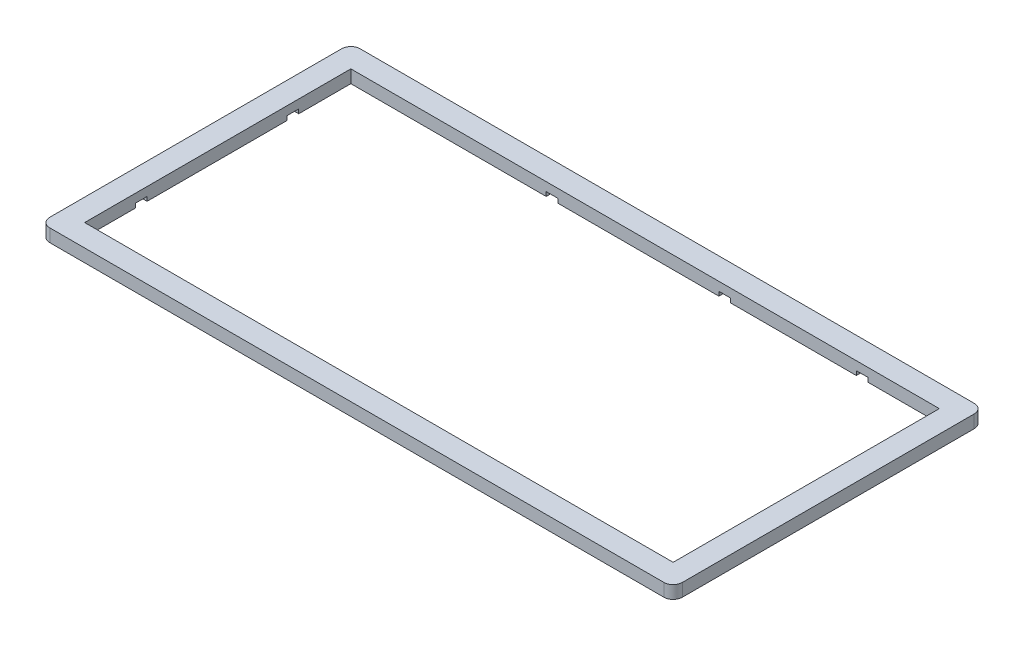
SolidWorks part; units mm, degrees
ref_plane "Front Plane" through (0, 0, 0) normal (0, 0, 1) x (1, 0, 0)
ref_plane "Top Plane" through (0, 0, 0) normal (0, 1, 0) x (1, 0, 0)
ref_plane "Right Plane" through (0, 0, 0) normal (1, 0, 0) x (0, 0, -1)
sketch "Sketch1" plane through (0, 0, 0) normal (0, 1, 0) x (1, 0, 0)
  line L0 (-142.8618, 0) -> (191.3602, 0) construction
  line L1 (0, 90.7825) -> (0, -132.7671) construction
  line L2 (-160.275, 78.7825) -> (160.275, 78.7825)
  line L3 (160.275, 78.7825) -> (160.275, -66.2175)
  line L4 (160.275, -66.2175) -> (-160.275, -66.2175)
  line L5 (-160.275, -66.2175) -> (-160.275, 78.7825)
  line L6 (-172.275, 90.7825) -> (172.275, 90.7825)
  line L7 (172.275, 90.7825) -> (172.275, -78.2175)
  line L8 (172.275, -78.2175) -> (-172.275, -78.2175)
  line L9 (-172.275, -78.2175) -> (-172.275, 90.7825)
  dimension "D1" = 320.55
  dimension "D2" = 145
  dimension "D3" = 12
  dimension "D4" = 12
  dimension "D5" = 12
  dimension "D6" = 12
extrude "Boss-Extrude1" add sketch "Sketch1" along normal blind 7
sketch "Sketch3" plane through (0, 0, 0) normal (0, -1, 0) x (1, 0, 0)
  line L0 (-22.72, -82.0825) -> (-47.57, -82.0825)
  line L1 (-22.72, -86.5825) -> (-22.72, -82.0825)
  line L2 (-78.72, -86.5825) -> (-22.72, -86.5825)
  line L3 (-78.72, -82.0825) -> (-78.72, -86.5825)
  line L4 (-53.87, -82.0825) -> (-78.72, -82.0825)
  line L5 (-53.87, -78.7825) -> (-53.87, -82.0825)
  line L6 (-47.57, -78.7825) -> (-53.87, -78.7825)
  line L7 (-47.57, -82.0825) -> (-47.57, -78.7825)
  line L16 (160.275, -78.7825) -> (-160.275, -78.7825) construction
  line L17 (-130.175, 66.2175) -> (-123.875, 66.2175)
  line L18 (146.225, -82.0825) -> (121.375, -82.0825)
  line L19 (146.225, -86.5825) -> (146.225, -82.0825)
  line L20 (90.225, -86.5825) -> (146.225, -86.5825)
  line L21 (90.225, -82.0825) -> (90.225, -86.5825)
  line L22 (115.075, -82.0825) -> (90.225, -82.0825)
  line L23 (115.075, -78.7825) -> (115.075, -82.0825)
  line L24 (121.375, -78.7825) -> (115.075, -78.7825)
  line L25 (121.375, -82.0825) -> (121.375, -78.7825)
  line L26 (71.33, -86.5825) -> (71.33, -82.0825)
  line L27 (15.33, -86.5825) -> (71.33, -86.5825)
  line L28 (15.33, -82.0825) -> (15.33, -86.5825)
  line L29 (40.18, -82.0825) -> (15.33, -82.0825)
  line L30 (40.18, -78.7825) -> (40.18, -82.0825)
  line L31 (46.48, -78.7825) -> (40.18, -78.7825)
  line L32 (46.48, -82.0825) -> (46.48, -78.7825)
  line L33 (71.33, -82.0825) -> (46.48, -82.0825)
  line L34 (-160.275, -78.7825) -> (-160.275, -50.3825) construction
  line L43 (-160.275, -44.0825) -> (-160.275, -50.3825)
  line L44 (-160.275, -44.0825) -> (-163.575, -44.0825)
  line L53 (163.575, 11.9175) -> (163.575, 32.2175)
  line L54 (-160.275, 66.2175) -> (160.275, 66.2175) construction
  line L55 (160.275, 66.2175) -> (160.275, -78.7825) construction
  line L56 (151.2867, -7.345) -> (183.3703, -7.345) construction
  line L57 (0, 81.7249) -> (0, 49.7201) construction
  line L58 (160.275, -40.5825) -> (163.575, -40.5825)
  line L59 (163.575, -40.5825) -> (163.575, -15.7325)
  line L60 (163.575, -15.7325) -> (168.075, -15.7325)
  line L61 (168.075, -15.7325) -> (168.075, -71.7325)
  line L62 (168.075, -71.7325) -> (163.575, -71.7325)
  line L63 (163.575, -71.7325) -> (163.575, -46.8825)
  line L64 (160.275, -46.8825) -> (163.575, -46.8825)
  line L65 (160.275, -40.5825) -> (160.275, -46.8825)
  line L66 (160.275, 32.2175) -> (163.575, 32.2175)
  line L68 (163.575, 58.8175) -> (168.075, 58.8175)
  line L69 (168.075, 58.8175) -> (168.075, 11.9175)
  line L70 (168.075, 11.9175) -> (163.575, 11.9175)
  line L72 (160.275, 38.5175) -> (163.575, 38.5175)
  line L73 (160.275, 32.2175) -> (160.275, 38.5175)
  line L74 (146.225, 74.0175) -> (146.225, 69.5175)
  line L75 (90.225, 74.0175) -> (146.225, 74.0175)
  line L76 (90.225, 69.5175) -> (90.225, 74.0175)
  line L77 (115.075, 69.5175) -> (90.225, 69.5175)
  line L78 (115.075, 66.2175) -> (115.075, 69.5175)
  line L79 (121.375, 66.2175) -> (115.075, 66.2175)
  line L80 (121.375, 69.5175) -> (121.375, 66.2175)
  line L81 (146.225, 69.5175) -> (121.375, 69.5175)
  line L82 (15.33, 74.0175) -> (71.33, 74.0175)
  line L83 (15.33, 69.5175) -> (15.33, 74.0175)
  line L84 (40.18, 69.5175) -> (15.33, 69.5175)
  line L85 (40.18, 66.2175) -> (40.18, 69.5175)
  line L86 (46.48, 66.2175) -> (40.18, 66.2175)
  line L87 (46.48, 69.5175) -> (46.48, 66.2175)
  line L88 (71.33, 69.5175) -> (46.48, 69.5175)
  line L89 (71.33, 74.0175) -> (71.33, 69.5175)
  line L106 (0, -99.7125) -> (0, -58.961) construction
  line L115 (163.575, 38.5175) -> (163.575, 58.8175)
  line L116 (-160.275, 66.2175) -> (160.275, 66.2175) construction
  line L117 (-160.275, -50.3825) -> (-163.575, -50.3825)
  line L118 (-163.575, -44.0825) -> (-163.575, -19.2325)
  line L119 (-163.575, -50.3825) -> (-163.575, -75.2325)
  line L120 (-163.575, -19.2325) -> (-168.075, -19.2325)
  line L121 (-168.075, -19.2325) -> (-168.075, -75.2325)
  line L122 (-168.075, -75.2325) -> (-163.575, -75.2325)
  line L123 (-160.275, -78.7825) -> (-160.275, 66.2175) construction
  line L124 (-160.275, 38.5175) -> (-160.275, 32.2175)
  line L125 (-160.275, 38.5175) -> (-163.575, 38.5175)
  line L126 (-160.275, 32.2175) -> (-163.575, 32.2175)
  line L127 (-163.575, 38.5175) -> (-163.575, 58.8175)
  line L128 (-163.575, 58.8175) -> (-168.075, 58.8175)
  line L129 (-168.075, 58.8175) -> (-168.075, 11.9175)
  line L130 (-168.075, 11.9175) -> (-163.575, 11.9175)
  line L131 (-163.575, 11.9175) -> (-163.575, 32.2175)
  line L132 (-160.275, 66.2175) -> (-160.275, 38.5175) construction
  line L133 (-123.875, 66.2175) -> (-123.875, 69.5175)
  line L134 (-123.875, 69.5175) -> (-99.025, 69.5175)
  line L135 (-99.025, 69.5175) -> (-99.025, 74.0175)
  line L136 (-99.025, 74.0175) -> (-155.025, 74.0175)
  line L137 (-155.025, 74.0175) -> (-155.025, 69.5175)
  line L138 (-155.025, 69.5175) -> (-130.175, 69.5175)
  line L139 (-130.175, 69.5175) -> (-130.175, 66.2175)
  line L140 (-160.275, 66.2175) -> (-130.175, 66.2175) construction
  line L141 (-55.375, 66.2175) -> (-49.075, 66.2175)
  line L142 (-49.075, 66.2175) -> (-49.075, 69.5175)
  line L143 (-49.075, 69.5175) -> (-24.225, 69.5175)
  line L144 (-24.225, 69.5175) -> (-24.225, 74.0175)
  line L145 (-24.225, 74.0175) -> (-80.225, 74.0175)
  line L146 (-80.225, 74.0175) -> (-80.225, 69.5175)
  line L147 (-80.225, 69.5175) -> (-55.375, 69.5175)
  line L148 (-55.375, 69.5175) -> (-55.375, 66.2175)
  line L149 (-123.875, 66.2175) -> (-55.375, 66.2175) construction
  line L150 (-47.57, -78.7825) -> (0, -78.7825) construction
  line L151 (160.275, -78.7825) -> (-160.275, -78.7825) construction
  line L152 (0, -78.7825) -> (40.18, -78.7825) construction
  dimension "D5" = 6.3
  dimension "D6" = 4.5
  dimension "D7" = 56
  dimension "D8" = 6.3
  dimension "D9" = 6.3
  dimension "D10" = 3.3
  dimension "D11" = 56
  dimension "D12" = 47.57
  dimension "D13" = 6.3
  dimension "D14" = 4.5
  dimension "D15" = 56
  dimension "D16" = 6.3
  dimension "D17" = 6.3
  dimension "D18" = 4.5
  dimension "D19" = 56
  dimension "D20" = 3.3
  dimension "D21" = 28.4
  dimension "D22" = 20.3
  dimension "D23" = 4.5
  dimension "D24" = 3.3
  dimension "D25" = 27.7
  dimension "D26" = 3.3
  dimension "D27" = 4.5
  dimension "D28" = 56
  dimension "D29" = 30.1
  dimension "D30" = 40.18
  dimension "D31" = 180
  dimension "56" = 56
  dimension "D32" = 6.3
  dimension "D33" = 38.9
  dimension "D34" = 6.3
  dimension "D35" = 27.7
  dimension "D36" = 31.9
  dimension "D37" = 56
  dimension "D38" = 38.9
  dimension "D39" = 6.3
  dimension "D40" = 3.3
  dimension "D41" = 4.5
  dimension "D42" = 40.18
  dimension "D43" = 6.3
  dimension "D44" = 3.3
  dimension "D45" = 46.9
  dimension "D46" = 6.3
  dimension "D47" = 3.3
  dimension "D48" = 4.5
  dimension "D49" = 3.3
  dimension "D50" = 4.5
  dimension "D51" = 3.3
  dimension "D52" = 4.5
  dimension "D53" = 56
  dimension "D54" = 4.5
  dimension "D55" = 3.3
  dimension "D56" = 4.5
  dimension "D57" = 3.3
  dimension "D58" = 56
  dimension "D59" = 68.5
  dimension "D60" = 180
fillet "Fillet1" radius 5 1 edges at (172.275, 3.5, 78.2175)
fillet "Fillet2" radius 5 1 edges at (-172.275, 3.5, -90.7825)
fillet "Fillet3" radius 5 1 edges at (-172.275, 3.5, 78.2175)
extrude "Cut-Extrude2" cut sketch "Sketch3" against normal blind 2.3
fillet "Fillet5" radius 5 1 edges at (172.275, 3.5, -90.7825)
sketch "Sketch4" plane through (0, 0, 0) normal (0, -1, 0) x (1, 0, 0)
  circle A8 centre (-165.5428, 71.4853) radius 1.325
  circle A9 centre (-89.625, 71.7675) radius 1.325
  circle A10 centre (80.7775, 71.7675) radius 1.325
  circle A11 centre (165.5328, 71.4853) radius 1.325
  circle A12 centre (165.5328, -84.0502) radius 1.325
  circle A13 centre (80.7775, -84.3325) radius 1.325
  circle A14 centre (-89.625, -84.0502) radius 1.325
  circle A15 centre (-165.5428, -84.0502) radius 1.325
  point P6 (-165.5428, 71.4853)
  point P7 (-89.625, 71.7675)
  point P9 (80.7775, 71.7675)
  point P11 (80.7775, -84.3325)
  point P12 (-89.625, -84.0502)
  point P13 (-165.5428, -84.0502)
  point P16 (165.5328, 71.4853)
  point P22 (165.5328, -84.0502)
extrude "Cut-Extrude3" cut sketch "Sketch4" against normal blind 4
